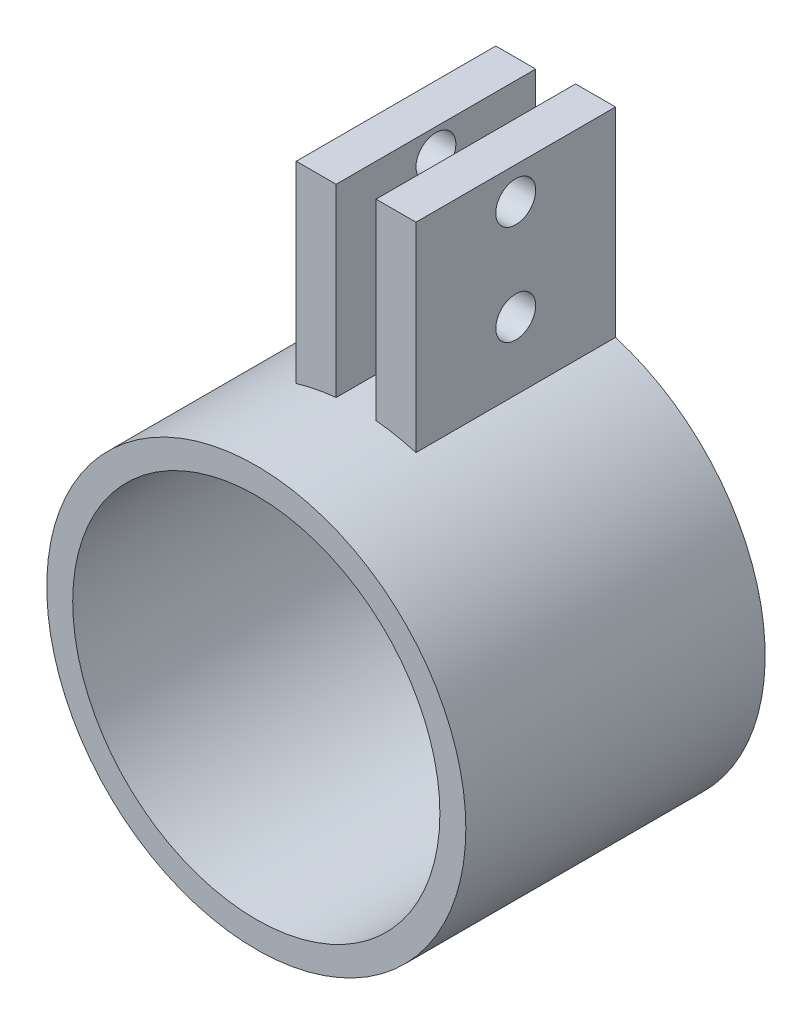
SolidWorks part; units mm, degrees
ref_plane "Front Plane" through (0, 0, 0) normal (0, 0, 1) x (1, 0, 0)
ref_plane "Top Plane" through (0, 0, 0) normal (0, 1, 0) x (1, 0, 0)
ref_plane "Right Plane" through (0, 0, 0) normal (1, 0, 0) x (0, 0, -1)
sketch "Sketch5" plane through (0, 0, 0) normal (0, 0, 1) x (1, 0, 0)
  circle A0 centre (0, 0) radius 9.2
  circle A1 centre (0, 0) radius 10.5
extrude "Boss-Extrude1" add sketch "Sketch5" along normal blind 15
sketch "Sketch6" plane through (0, 0, 0) normal (0, 0, 1) x (1, 0, 0)
  circle A0 centre (0, 0) radius 10.5
extrude "Boss-Extrude2" add sketch "Sketch6" along normal blind 2
sketch "Sketch7" plane through (0, 0, 0) normal (0, 0, -1) x (-1, 0, 0)
  line L0 (-3, 10.0623) -> (-3, 20.0623)
  circle A0 centre (0, 0) radius 10.5 construction
  dimension "D1" = 10
  dimension "D2" = 3
sketch "Sketch8" plane through (0, 0, 0) normal (0, 0, -1) x (-1, 0, 0)
  line L0 (3, 10.0623) -> (3, 19.7082)
  circle A0 centre (0, 0) radius 10.5 construction
  dimension "D1" = 3
extrude "Extrude-Thin1" add sketch "Sketch7" against normal blind 10 thin
extrude "Extrude-Thin2" add sketch "Sketch8" against normal blind 10 thin thin type one direction reverse wall 2
sketch "Sketch9" plane through (-3, 0, 0) normal (-1, 0, 0) x (0, 0, 1)
  line L0 (0, 10.0623) -> (0, 19.7082) construction
  circle A0 centre (5, 13.4523) radius 1
  circle A1 centre (5, 18.4523) radius 1
  dimension "D1" = 5
  dimension "D2" = 5
  dimension "D3" = 3
  dimension "D4" = 5
extrude "Cut-Extrude1" cut sketch "Sketch9" against normal through all both and the other way through all
